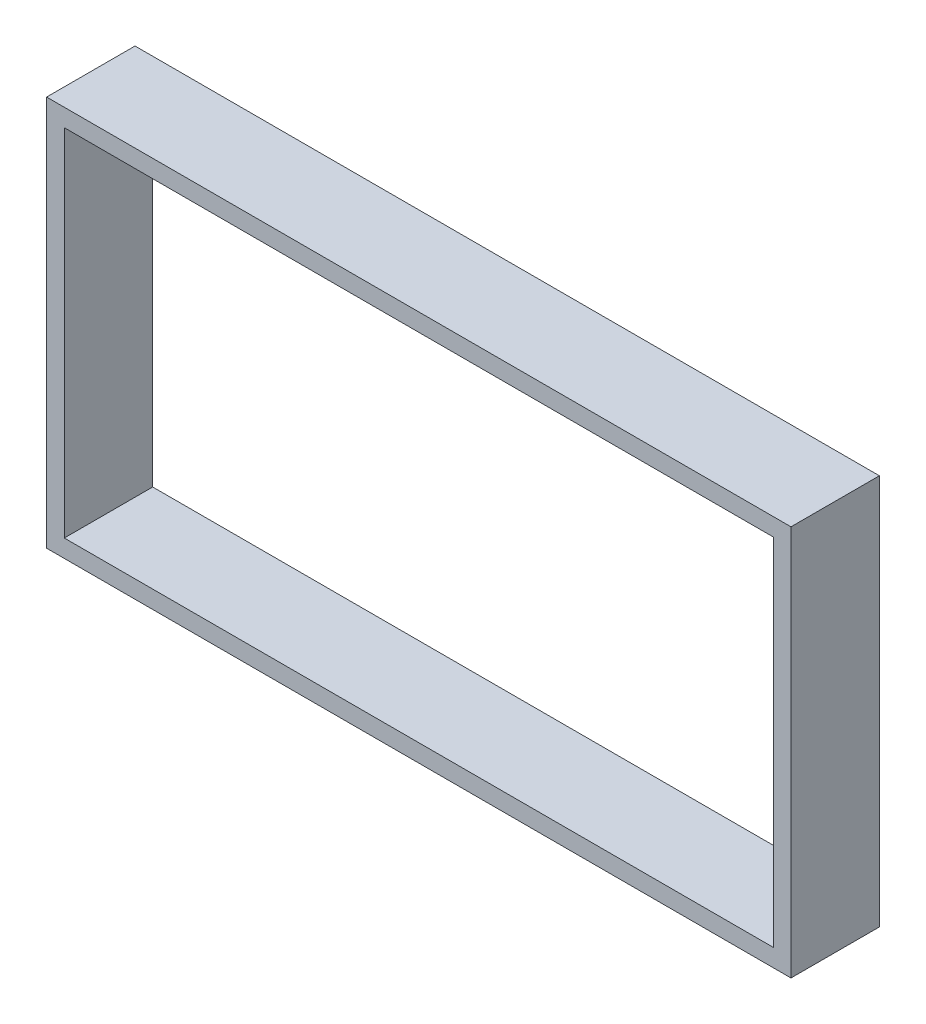
SolidWorks part; units mm, degrees
ref_plane "前视基准面" through (0, 0, 0) normal (0, 0, 1) x (1, 0, 0)
ref_plane "上视基准面" through (0, 0, 0) normal (0, 1, 0) x (1, 0, 0)
ref_plane "右视基准面" through (0, 0, 0) normal (1, 0, 0) x (0, 0, -1)
sketch "草图1" plane through (0, 0, 0) normal (0, 0, 1) x (1, 0, 0)
  line L1 (-47.2727, 13.7455) -> (36.9273, 13.7455)
  line L2 (-47.2727, 13.7455) -> (-47.2727, -30.4545)
  line L3 (-47.2727, -30.4545) -> (36.9273, -30.4545)
  line L4 (36.9273, 13.7455) -> (36.9273, -30.4545)
  line L5 (-45.2727, 11.7455) -> (34.9273, 11.7455)
  line L6 (-45.2727, 11.7455) -> (-45.2727, -28.4545)
  line L7 (-45.2727, -28.4545) -> (34.9273, -28.4545)
  line L8 (34.9273, 11.7455) -> (34.9273, -28.4545)
  dimension "D1" = 2
  dimension "D2" = 2
  dimension "D3" = 2
  dimension "D4" = 2
  dimension "D5" = 40.2
  dimension "D6" = 80.2
extrude "凸台-拉伸1" add sketch "草图1" along normal blind 10
